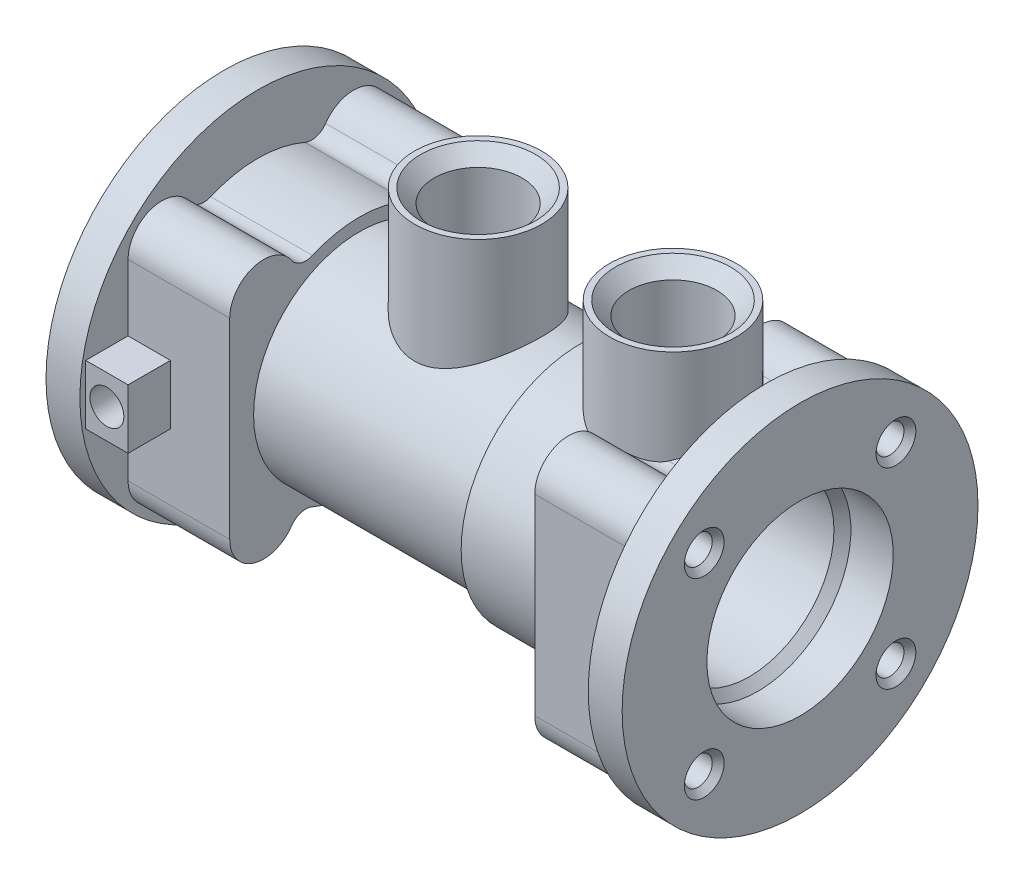
SolidWorks part; units mm, degrees
ref_plane "Спереди" through (0, 0, 0) normal (0, 0, 1) x (1, 0, 0)
ref_plane "Сверху" through (0, 0, 0) normal (0, 1, 0) x (1, 0, 0)
ref_plane "Справа" through (0, 0, 0) normal (1, 0, 0) x (0, 0, -1)
sketch "Эскиз1" plane through (0, 0, 0) normal (0, 0, 1) x (1, 0, 0)
  line L0 (0, 0) -> (74.2012, 0) construction
  line L1 (0, 21) -> (0, 11)
  line L2 (0, 11) -> (7, 11)
  line L3 (7, 11) -> (8, 10)
  line L4 (8, 10) -> (35, 10)
  line L5 (35, 10) -> (35, 9)
  line L6 (35, 9) -> (36, 9)
  line L7 (36, 9) -> (36, 8)
  line L8 (0, 21) -> (4, 21)
  line L9 (4, 21) -> (4, 14)
  line L10 (4, 14) -> (11, 14)
  line L11 (11, 14) -> (11, 12.5)
  line L12 (11, 12.5) -> (42, 12.5)
  line L13 (42, 12.5) -> (42, 14)
  line L14 (42, 14) -> (64, 14)
  line L15 (64, 14) -> (64, 21)
  line L16 (64, 21) -> (68, 21)
  line L17 (68, 21) -> (68, 11)
  line L18 (68, 11) -> (63, 11)
  line L19 (63, 11) -> (62, 10)
  line L20 (62, 10) -> (43, 10)
  line L21 (43, 10) -> (43, 6)
  line L22 (36, 8) -> (40.2, 8)
  line L23 (40.2, 8) -> (40.2, 6)
  line L24 (40.2, 6) -> (43, 6)
  dimension "D1" = 22
  dimension "D2" = 42
  dimension "D3" = 28
  dimension "D4" = 4
  dimension "D5" = 7
  dimension "D6" = 20
  dimension "D7" = 45
  dimension "D8" = 7
  dimension "D9" = 25
  dimension "D10" = 18
  dimension "D11" = 35
  dimension "D12" = 68
  dimension "D13" = 22
  dimension "D14" = 20
  dimension "D15" = 5
  dimension "D16" = 12
  dimension "D17" = 16
  dimension "D18" = 36
  dimension "D19" = 25
  dimension "D20" = 40.2
  dimension "D21" = 28
  dimension "D22" = 26
revolve "Повернуть1" add sketch "Эскиз1" angle 360 about L0
sketch "Эскиз2" plane through (4, 0, 0) normal (1, 0, 0) x (0, 0, -1)
  line L0 (0, 0) -> (16, 0) construction
  line L1 (0, 0) -> (0, 23.8463) construction
  line L2 (15.3137, 11.3137) -> (15.3137, 0)
  line L3 (0, 12.5) -> (0, 15.2687) construction
  line L4 (12.5, 0) -> (15.3137, 0)
  line L5 (-15.3137, 11.3137) -> (-15.3137, 0)
  line L6 (-12.5, 0) -> (-15.3137, 0)
  circle A0 centre (0, 0) radius 16 construction
  circle A1 centre (11.3137, 11.3137) radius 4 construction
  arc A2 (-5.557, 12.8499) -> (5.557, 12.8499) centre (0, 0) cw
  arc A4 (15.3137, 11.3137) -> (8.0051, 13.5616) centre (11.3137, 11.3137) ccw
  arc A5 (5.557, 12.8499) -> (8.0051, 13.5616) centre (6.3508, 14.6856) ccw
  arc A6 (-12.5, 0) -> (12.5, 0) centre (0, 0) cw
  circle A7 centre (0, 0) radius 12.5 construction
  arc A8 (-5.557, 12.8499) -> (-8.0051, 13.5616) centre (-6.3508, 14.6856) cw
  arc A9 (-15.3137, 11.3137) -> (-8.0051, 13.5616) centre (-11.3137, 11.3137) cw
  circle A10 centre (0, 0) radius 14 construction
  dimension "D1" = 32
  dimension "D3" = 8
  dimension "D4" = 4
  dimension "D2" = 45
extrude "Бобышка-Вытянуть1" add sketch "Эскиз2" along normal blind 12
mirror "Зеркальное отражение6" about plane through (16, 0, 12.5) normal (0, 1, 0) of "Бобышка-Вытянуть1"
ref_plane "Плоскость1" through (34, 0, 0) normal (-1, 0, 0) x (0, 0, 1)
sketch "Эскиз3" plane through (64, 0, 0) normal (-1, 0, 0) x (0, 0, 1)
  line L2 (-15.3137, 11.3137) -> (-15.3137, -11.3137)
  line L3 (15.3137, -11.3137) -> (15.3137, 11.3137)
  line L4 (-15.3137, 11.3137) -> (-15.3137, -11.3137)
  line L5 (15.3137, -11.3137) -> (15.3137, 11.3137)
  circle A0 centre (0, 0) radius 14 construction
  circle A1 centre (0, 0) radius 14
  arc A10 (-15.3137, -11.3137) -> (-8.0051, -13.5616) centre (-11.3137, -11.3137) ccw
  arc A11 (-8.0051, 13.5616) -> (-15.3137, 11.3137) centre (-11.3137, 11.3137) ccw
  arc A12 (-8.0051, 13.5616) -> (-5.557, 12.8499) centre (-6.3508, 14.6856) ccw
  arc A13 (5.557, 12.8499) -> (-5.557, 12.8499) centre (0, 0) ccw
  arc A14 (5.557, 12.8499) -> (8.0051, 13.5616) centre (6.3508, 14.6856) ccw
  arc A15 (15.3137, 11.3137) -> (8.0051, 13.5616) centre (11.3137, 11.3137) ccw
  arc A16 (8.0051, -13.5616) -> (15.3137, -11.3137) centre (11.3137, -11.3137) ccw
  arc A17 (8.0051, -13.5616) -> (5.557, -12.8499) centre (6.3508, -14.6856) ccw
  arc A18 (-5.557, -12.8499) -> (5.557, -12.8499) centre (0, 0) ccw
  arc A19 (-5.557, -12.8499) -> (-8.0051, -13.5616) centre (-6.3508, -14.6856) ccw
  arc A20 (-15.3137, -11.3137) -> (-8.0051, -13.5616) centre (-11.3137, -11.3137) ccw
  arc A21 (-8.0051, 13.5616) -> (-15.3137, 11.3137) centre (-11.3137, 11.3137) ccw
  arc A22 (-8.0051, 13.5616) -> (-5.557, 12.8499) centre (-6.3508, 14.6856) ccw
  arc A23 (5.557, 12.8499) -> (-5.557, 12.8499) centre (0, 0) ccw
  arc A24 (5.557, 12.8499) -> (8.0051, 13.5616) centre (6.3508, 14.6856) ccw
  arc A25 (15.3137, 11.3137) -> (8.0051, 13.5616) centre (11.3137, 11.3137) ccw
  arc A26 (8.0051, -13.5616) -> (15.3137, -11.3137) centre (11.3137, -11.3137) ccw
  arc A27 (8.0051, -13.5616) -> (5.557, -12.8499) centre (6.3508, -14.6856) ccw
  arc A28 (-5.557, -12.8499) -> (5.557, -12.8499) centre (0, 0) ccw
  arc A29 (-5.557, -12.8499) -> (-8.0051, -13.5616) centre (-6.3508, -14.6856) ccw
  dimension "D1" = 0
extrude "Бобышка-Вытянуть2" add sketch "Эскиз3" along normal blind 12 contours A27 A26 L5 A25 A24 A1 | A29 A1 A22 A21 L4 A20
ref_plane "Плоскость2" through (0, 24, 0) normal (0, 1, 0) x (1, 0, 0)
sketch "Эскиз4" plane through (0, 24, 0) normal (0, 1, 0) x (1, 0, 0)
  line L0 (68, -21) -> (68, 21) construction
  circle A0 centre (30, 0) radius 7.5
  circle A1 centre (53, 0) radius 7.5
  dimension "D1" = 15
  dimension "D2" = 15
  dimension "D3" = 23
extrude "Бобышка-Вытянуть3" add sketch "Эскиз4" against normal up to surface (14 mm away)
sketch "Эскиз5" plane through (0, 24, 0) normal (0, 1, 0) x (1, 0, 0)
  circle A0 centre (53, 0) radius 5.188
  circle A1 centre (30, 0) radius 5.188
  dimension "D1" = 10.376
extrude "Вырез-Вытянуть1" cut sketch "Эскиз5" against normal up to surface (20.9859 mm away)
cosmetic thread "Условное изображение резьбы1" parameters "D2"=12
cosmetic thread "Условное изображение резьбы2" parameters "D2"=12
chamfer "Фаска1" distance 1.6 angle 45 2 edges at (30, 24, 5.188) (53, 24, 5.188)
sketch "Эскиз6" plane through (0, 0, 0) normal (-1, 0, 0) x (0, 0, 1)
  circle A0 centre (0, 0) radius 16 construction
  point P0 (11.3137, 11.3137)
  point P2 (-11.3137, 11.3137)
  point P4 (-11.3137, -11.3137)
  point P5 (11.3137, -11.3137)
sketch "Эскиз8" plane through (68, 0, 0) normal (1, 0, 0) x (0, 0, -1)
  point P0 (-11.3137, -11.3137)
  point P2 (11.3137, -11.3137)
  point P4 (-11.3137, 11.3137)
  point P6 (11.3137, 11.3137)
hole_wizard "Отверстие обработанное метчиком M41" positions "Трехмерный эскиз1" profile "Эскиз9" tap size "M4" standard "GOST"
sketch3d "Трехмерный эскиз1"
  point P0 (68, -11.3137, 11.3137)
  point P3 (68, -11.3137, -11.3137)
  point P6 (68, 11.3137, -11.3137)
  point P9 (68, 11.3137, 11.3137)
  point P12 (0, 11.3137, -11.3137)
  point P15 (0, -11.3137, -11.3137)
  point P18 (0, -11.3137, 11.3137)
  point P21 (0, 11.3137, 11.3137)
sketch "Эскиз9" plane through (68, -11.3137, 11.3137) normal (0, 1, 0) x (0, 0, -1)
  line L0 (0, 0) -> (0, 12.9914)
  line L1 (0, 12.9914) -> (1.65, 12)
  line L2 (1.65, 12) -> (1.65, 0)
  line L5 (1.65, 0) -> (0, 0)
  line L10 (0, 12.9914) -> (-1.65, 12) construction
  line L11 (0, -6.35) -> (0, 107.95) construction
  dimension "Диаметр сверла" = 3.3
  dimension "Глубина сверла" = 12
  dimension "Угол заточки сверла" = 118
cosmetic thread "Отверстие резьбы1" parameters "D1"=8, "D2"=4
cosmetic thread "Отверстие резьбы2" parameters "D1"=8, "D2"=4
cosmetic thread "Отверстие резьбы3" parameters "D1"=8, "D2"=4
cosmetic thread "Отверстие резьбы4" parameters "D1"=8, "D2"=4
cosmetic thread "Отверстие резьбы5" parameters "D1"=8, "D2"=4
cosmetic thread "Отверстие резьбы6" parameters "D1"=8, "D2"=4
cosmetic thread "Отверстие резьбы7" parameters "D1"=8, "D2"=4
cosmetic thread "Отверстие резьбы8" parameters "D1"=8, "D2"=4
sketch "Эскиз11" plane through (0, 0, 15.3137) normal (0, 0, 1) x (1, 0, 0)
  line L0 (4, 11.3137) -> (4, -11.3137) construction
  line L1 (9, -3.5) -> (4, -3.5)
  line L2 (9, -3.5) -> (9, 3.5)
  line L3 (9, 3.5) -> (4, 3.5)
  line L4 (4, -3.5) -> (4, 3.5)
  line L5 (9, -3.5) -> (4, 3.5) construction
  line L6 (9, 3.5) -> (4, -3.5) construction
  point P0 (6.5, 0)
  dimension "D1" = 7
  dimension "D2" = 5
extrude "Бобышка-Вытянуть4" add sketch "Эскиз11" along normal blind 5
sketch "Эскиз12" plane through (0, 0, 20.3137) normal (0, 0, 1) x (1, 0, 0)
  line L0 (4, 0) -> (9, 0) construction
  line L2 (9, -3.5) -> (9, 3.5) construction
  line L3 (4, -21) -> (4, 21) construction
  circle A0 centre (6.5, 0) radius 2
  dimension "D1" = 4
extrude "Вырез-Вытянуть2" cut sketch "Эскиз12" against normal up to surface (10.3137 mm away)
chamfer "Фаска2" distance 0.7 angle 45 8 edges at (68, -11.3137, 9.6637) (68, -11.3137, -12.9637) (68, 11.3137, -12.9637) (68, 11.3137, 9.6637) (0, -11.3137, 12.9637) (0, -11.3137, -9.6637) (0, 11.3137, -9.6637) (0, 11.3137, 12.9637)
